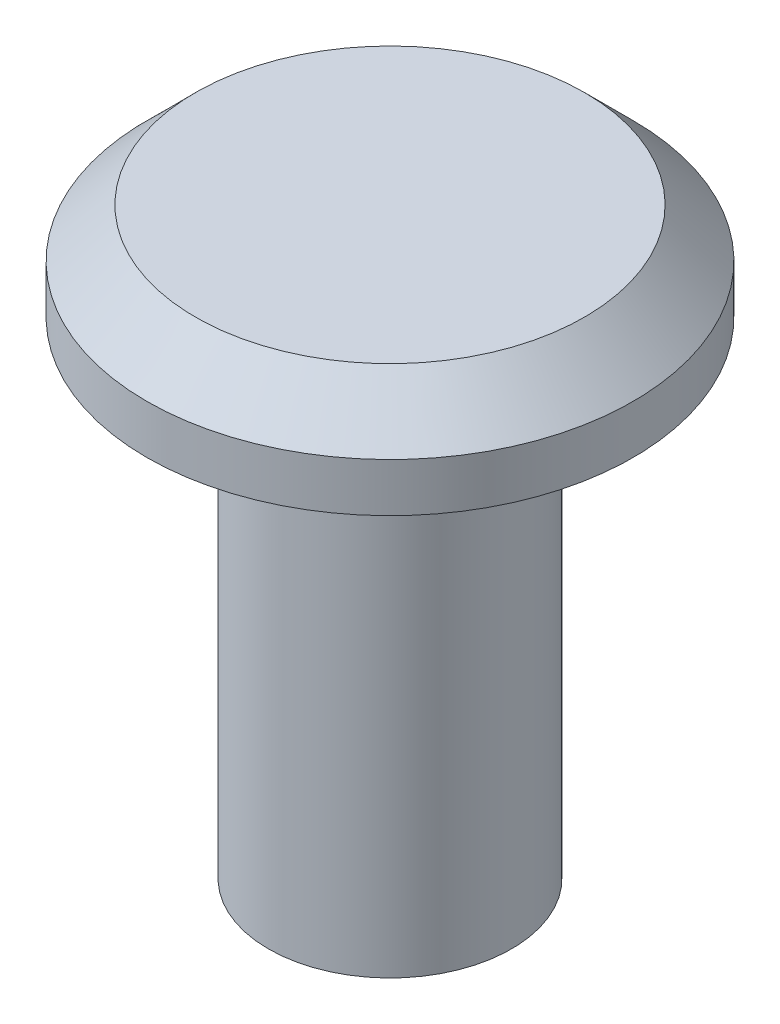
SolidWorks part; units mm, degrees
ref_plane "Plan de face" through (0, 0, 0) normal (0, 0, 1) x (1, 0, 0)
ref_plane "Plan de dessus" through (0, 0, 0) normal (0, 1, 0) x (1, 0, 0)
ref_plane "Plan de droite" through (0, 0, 0) normal (1, 0, 0) x (0, 0, -1)
sketch "Esquisse1" plane through (0, 0, 0) normal (0, 0, 1) x (1, 0, 0)
  line L0 (0, 0) -> (0, 12)
  line L1 (0, 12) -> (-4, 12)
  line L2 (-4, 12) -> (-5, 11)
  line L3 (-5, 11) -> (-5, 10)
  line L4 (-5, 10) -> (-2.5, 10)
  line L5 (-2.5, 10) -> (-2.5, 0)
  line L6 (-2.5, 0) -> (0, 0)
  dimension "D1" = 2.5
  dimension "D2" = 10
  dimension "D3" = 2.5
  dimension "D4" = 4
  dimension "D5" = 1
  dimension "D6" = 12
revolve "Révolution1" add sketch "Esquisse1" angle 360 about L0
